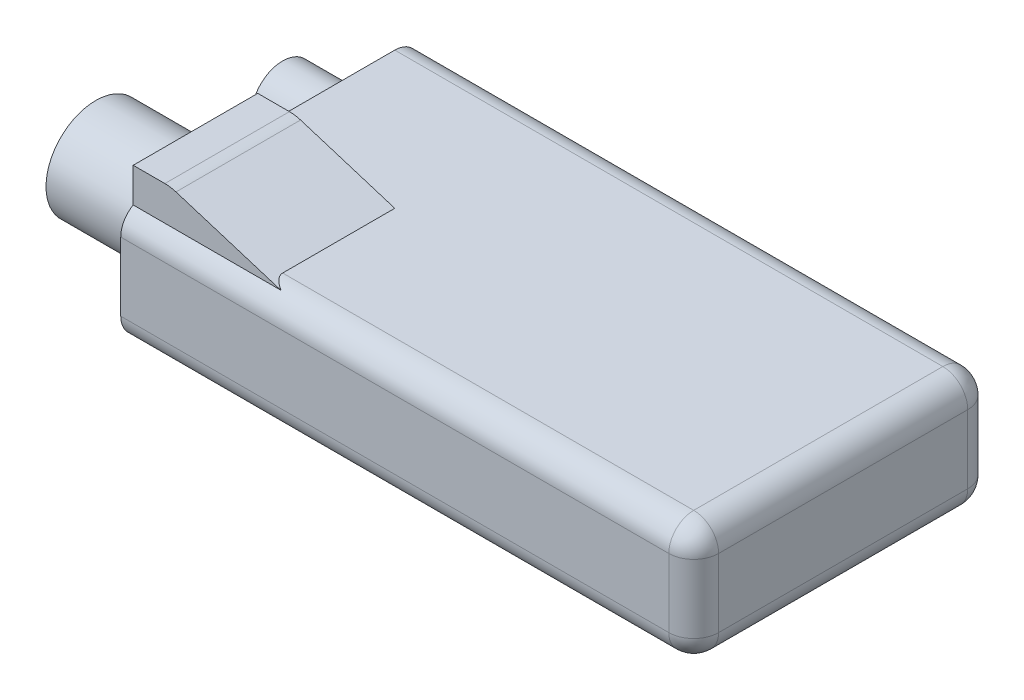
SolidWorks part; units mm, degrees
material "PVC 僵硬"
ref_plane "前视基准面" through (0, 0, 0) normal (0, 0, 1) x (1, 0, 0)
ref_plane "上视基准面" through (0, 0, 0) normal (0, 1, 0) x (1, 0, 0)
ref_plane "右视基准面" through (0, 0, 0) normal (1, 0, 0) x (0, 0, -1)
sketch "草图1" plane through (0, 0, 0) normal (0, 1, 0) x (1, 0, 0)
  line L0 (46.7841, 0) -> (-41.5568, 0) construction
  line L1 (-23, 12) -> (23, 12)
  line L2 (-23, 12) -> (-23, -12)
  line L3 (-23, -12) -> (23, -12)
  line L4 (23, 12) -> (23, -12)
  line L5 (-23, 12) -> (23, -12) construction
  line L6 (-23, -12) -> (23, 12) construction
  point P0 (0, 0)
  dimension "D1" = 46
  dimension "D2" = 24
extrude "凸台-拉伸1" add sketch "草图1" along normal blind 9.5
sketch "草图2" plane through (-23, 0, 0) normal (-1, 0, 0) x (0, 0, 1)
  line L0 (-12, 0) -> (12, 0) construction
  line L2 (12, 9.5) -> (12, 0) construction
  circle A0 centre (6, 6) radius 4
  point P4 (12, 4.75)
  dimension "D1" = 8
  dimension "D2" = 6
  dimension "D3" = 6
extrude "凸台-拉伸2" add sketch "草图2" along normal blind 8
sketch "草图4" plane through (-23, 0, 0) normal (-1, 0, 0) x (0, 0, 1)
  line L0 (6, 6) -> (6, 12) construction
  line L2 (11, 6.0075) -> (1, 6.0075)
  line L3 (11, 6.0075) -> (11, 11.9925)
  line L4 (11, 11.9925) -> (1, 11.9925)
  line L5 (1, 6.0075) -> (1, 11.9925)
  line L6 (11, 6.0075) -> (1, 11.9925) construction
  line L7 (11, 11.9925) -> (1, 6.0075) construction
  point P3 (6, 9)
  dimension "D1" = 6
  dimension "D2" = 3
  dimension "D3" = 10
extrude "凸台-拉伸3" add sketch "草图4" against normal blind 3
sketch "草图5" plane through (0, 0, 11) normal (0, 0, 1) x (1, 0, 0)
  line L0 (-20, 11.9925) -> (-20, 9.5)
  line L1 (-20, 9.5) -> (-12, 9.5)
  line L2 (-23, 9.5) -> (23, 9.5) construction
  line L3 (-12, 9.5) -> (-20, 11.9925)
  dimension "D1" = 8
extrude "凸台-拉伸4" add sketch "草图5" against normal up to surface (10 mm away) up to face at (-21.5, 10.7462, 1)
sketch "草图6" plane through (-23, 0, 0) normal (-1, 0, 0) x (0, 0, 1)
  circle A0 centre (-7, 4.7494) radius 2.5
  circle A1 centre (6, 6) radius 4 construction
  dimension "D2" = 5
  dimension "D1" = 13
extrude "凸台-拉伸5" add sketch "草图6" along normal blind 6
fillet "圆角1" radius 3 1 edges at (-20, 11.9925, 6)
fillet "圆角5" radius 2 4 edges at (0, 0, 12) (0, 0, -12) (0, 9.5, -12) (0, 9.5, 12)
fillet "圆角6" radius 2 8 edges at (23, 8.9142, 11.4142) (23, 9.5, 0) (23, 8.9142, -11.4142) (23, 4.75, -12) (23, 0.5858, -11.4142) (23, 0, 0) (23, 0.5858, 11.4142) (23, 4.75, 12)
